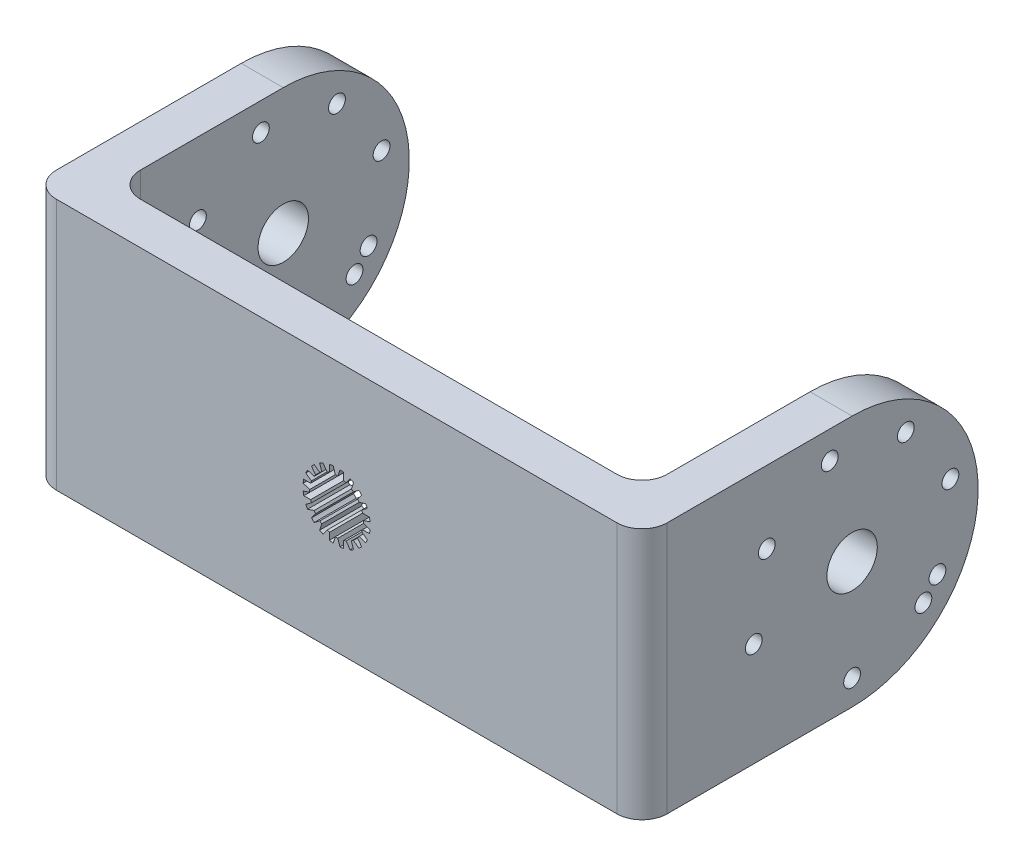
SolidWorks part; units mm, degrees
ref_plane "Front Plane" through (0, 0, 0) normal (0, 0, 1) x (1, 0, 0)
ref_plane "Top Plane" through (0, 0, 0) normal (0, 1, 0) x (1, 0, 0)
ref_plane "Right Plane" through (0, 0, 0) normal (1, 0, 0) x (0, 0, -1)
sketch "Sketch1" plane through (0, 0, 0) normal (0, 0, 1) x (1, 0, 0)
  line L0 (36.35, -15) -> (36.35, 15)
  line L1 (-36.35, -15) -> (-36.35, 15)
  line L2 (0, 0) -> (-36.35, 0)
  line L3 (0, 0) -> (36.35, 0)
  line L4 (-36.35, 15) -> (36.35, 15)
  line L5 (-36.35, -15) -> (36.35, -15)
  circle A0 centre (0, 0) radius 5
  point P10 (-36.35, 0)
  point P11 (36.35, 0)
  dimension "D1" = 10
  dimension "D2" = 30
  dimension "D4" = 36.35
  dimension "D5" = 36.35
extrude "Boss-Extrude1" add sketch "Sketch1" along normal blind 5 contours A0 L3 L0 L4 L1 L2 | L3 A0 L2 | L2 A0 L3 | A0 L2 L1 L5 L0 L3
sketch "Sketch4" plane through (0, 0, 0) normal (0, 0, -1) x (-1, 0, 0)
  line L0 (36.35, 15) -> (-36.35, 15) construction
  line L1 (-36.35, -15) -> (-31.35, -15)
  line L2 (-36.35, -15) -> (-36.35, 15)
  line L3 (-36.35, 15) -> (-31.35, 15)
  line L4 (-31.35, -15) -> (-31.35, 15)
  dimension "D1" = 5
extrude "Boss-Extrude4" add sketch "Sketch4" along normal blind 35
sketch "Sketch5" plane through (36.35, 0, 0) normal (1, 0, 0) x (0, 0, -1)
  line L0 (35, 0) -> (20, 0)
  line L1 (35, 15) -> (35, -15) construction
  circle A0 centre (20, 0) radius 15
  circle A1 centre (20, 0) radius 3
  dimension "D2" = 6
  dimension "D1" = 15
extrude "Cut-Extrude2" cut sketch "Sketch5" against normal blind 40
sketch "Sketch6" plane through (31.35, 0, 0) normal (-1, 0, 0) x (0, 0, 1)
  line L0 (-35, 15) -> (0, 15) construction
  line L1 (-35, -15) -> (0, -15) construction
  line L2 (-20, 15) -> (-35, 15)
  line L3 (-35, 15) -> (-35, -15)
  line L4 (-35, -15) -> (-20, -15)
  arc A0 (-20, 15) -> (-20, -15) centre (-20, 0) ccw
  circle A1 centre (-20, 0) radius 15 construction
  line M7 (0, 15) -> (-35, 15)
  line M8 (-35, 15) -> (-35, -15)
  line M9 (-35, -15) -> (0, -15)
extrude "Cut-Extrude3" cut sketch "Sketch6" against normal blind 10 contours A0 M7 M8 | A0 L3 M9
sketch "Sketch7" plane through (31.35, 0, 0) normal (-1, 0, 0) x (0, 0, 1)
  circle A0 centre (-31.7015, 2.6598) radius 1
  circle A1 centre (-17.3402, 11.7015) radius 1
  circle A2 centre (-9.845, 6.3935) radius 1
  circle A3 centre (-30.155, -6.3935) radius 1
  circle A4 centre (-8.2985, -2.6598) radius 1
  circle A6 centre (-26.3935, 10.155) radius 1
  circle A7 centre (-28.4853, -8.4853) radius 1
  circle A8 centre (-20, -12) radius 1
extrude "Cut-Extrude4" cut sketch "Sketch7" against normal blind 10
fillet "Fillet2" radius 3 1 edges at (36.35, 0, 5)
fillet "Fillet3" radius 3 1 edges at (31.35, 0, 0)
mirror "Mirror2" about plane through (0, 0, 0) normal (1, 0, 0) of "Cut-Extrude3", "Cut-Extrude2", "Boss-Extrude4", "Cut-Extrude4"
fillet "Fillet5" radius 3 1 edges at (-36.35, 0, 5)
fillet "Fillet6" radius 3 1 edges at (-31.35, 0, 0)
sketch "Sketch9" plane through (0, 0, 5) normal (0, 0, 1) x (1, 0, 0)
  line L0 (3.9776, 0.4069) -> (3.1976, 0.1569)
  line L1 (3.1976, 0.1569) -> (3.1976, -0.1431)
  line L2 (3.1976, -0.1431) -> (3.9776, -0.3931)
  line L3 (3.1976, 0.0069) -> (-0.0024, 0.0069) construction
  line L4 (3.9064, -0.8426) -> (3.0874, -0.8393)
  line L5 (3.0874, -0.8393) -> (2.9947, -1.1246)
  line L6 (2.9947, -1.1246) -> (3.6592, -1.6034)
  line L7 (3.4526, -2.0089) -> (2.6747, -1.7527)
  line L8 (2.6747, -1.7527) -> (2.4983, -1.9954)
  line L9 (2.4983, -1.9954) -> (2.9824, -2.6561)
  line L10 (2.6606, -2.9778) -> (1.9999, -2.4938)
  line L11 (1.9999, -2.4938) -> (1.7572, -2.6701)
  line L12 (1.7572, -2.6701) -> (2.0134, -3.4481)
  line L13 (1.6079, -3.6547) -> (1.1292, -2.9901)
  line L14 (1.1292, -2.9901) -> (0.8438, -3.0828)
  line L15 (0.8438, -3.0828) -> (0.8471, -3.9019)
  line L16 (0.3976, -3.9731) -> (0.1476, -3.1931)
  line L17 (0.1476, -3.1931) -> (-0.1524, -3.1931)
  line L18 (-0.1524, -3.1931) -> (-0.4024, -3.9731)
  line L19 (-0.8518, -3.9019) -> (-0.8485, -3.0828)
  line L20 (-0.8485, -3.0828) -> (-1.1339, -2.9901)
  line L21 (-1.1339, -2.9901) -> (-1.6126, -3.6547)
  line L22 (-2.0181, -3.4481) -> (-1.7619, -2.6701)
  line L23 (-1.7619, -2.6701) -> (-2.0046, -2.4938)
  line L24 (-2.0046, -2.4938) -> (-2.6653, -2.9778)
  line L25 (-2.9871, -2.6561) -> (-2.503, -1.9954)
  line L26 (-2.503, -1.9954) -> (-2.6794, -1.7527)
  line L27 (-2.6794, -1.7527) -> (-3.4573, -2.0089)
  line L28 (-3.6639, -1.6034) -> (-2.9994, -1.1246)
  line L29 (-2.9994, -1.1246) -> (-3.0921, -0.8393)
  line L30 (-3.0921, -0.8393) -> (-3.9111, -0.8426)
  line L31 (-3.9823, -0.3931) -> (-3.2024, -0.1431)
  line L32 (-3.2024, -0.1431) -> (-3.2024, 0.1569)
  line L33 (-3.2024, 0.1569) -> (-3.9823, 0.4069)
  line L34 (-3.9111, 0.8563) -> (-3.0921, 0.8531)
  line L35 (-3.0921, 0.8531) -> (-2.9994, 1.1384)
  line L36 (-2.9994, 1.1384) -> (-3.6639, 1.6172)
  line L37 (-3.4573, 2.0226) -> (-2.6794, 1.7664)
  line L38 (-2.6794, 1.7664) -> (-2.503, 2.0092)
  line L39 (-2.503, 2.0092) -> (-2.9871, 2.6699)
  line L40 (-2.6653, 2.9916) -> (-2.0046, 2.5076)
  line L41 (-2.0046, 2.5076) -> (-1.7619, 2.6839)
  line L42 (-1.7619, 2.6839) -> (-2.0181, 3.4619)
  line L43 (-1.6126, 3.6684) -> (-1.1339, 3.0039)
  line L44 (-1.1339, 3.0039) -> (-0.8485, 3.0966)
  line L45 (-0.8485, 3.0966) -> (-0.8518, 3.9157)
  line L46 (-0.4024, 3.9868) -> (-0.1524, 3.2069)
  line L47 (-0.1524, 3.2069) -> (0.1476, 3.2069)
  line L48 (0.1476, 3.2069) -> (0.3976, 3.9868)
  line L49 (0.8471, 3.9157) -> (0.8438, 3.0966)
  line L50 (0.8438, 3.0966) -> (1.1292, 3.0039)
  line L51 (1.1292, 3.0039) -> (1.6079, 3.6684)
  line L52 (2.0134, 3.4619) -> (1.7572, 2.6839)
  line L53 (1.7572, 2.6839) -> (1.9999, 2.5076)
  line L54 (1.9999, 2.5076) -> (2.6606, 2.9916)
  line L55 (2.9824, 2.6699) -> (2.4983, 2.0092)
  line L56 (2.4983, 2.0092) -> (2.6747, 1.7664)
  line L57 (2.6747, 1.7664) -> (3.4526, 2.0226)
  line L58 (3.6592, 1.6172) -> (2.9947, 1.1384)
  line L59 (2.9947, 1.1384) -> (3.0874, 0.8531)
  line L60 (3.0874, 0.8531) -> (3.9064, 0.8563)
  arc A0 (-2.6653, 2.9916) -> (-2.9871, 2.6699) centre (-0.0024, 0.0069) ccw
  arc A1 (-3.4573, 2.0226) -> (-3.6639, 1.6172) centre (-0.0024, 0.0069) ccw
  arc A2 (-3.9111, 0.8563) -> (-3.9823, 0.4069) centre (-0.0024, 0.0069) ccw
  arc A3 (-3.9823, -0.3931) -> (-3.9111, -0.8426) centre (-0.0024, 0.0069) ccw
  arc A4 (-3.6639, -1.6034) -> (-3.4573, -2.0089) centre (-0.0024, 0.0069) ccw
  arc A5 (-2.9871, -2.6561) -> (-2.6653, -2.9778) centre (-0.0024, 0.0069) ccw
  arc A6 (-2.0181, -3.4481) -> (-1.6126, -3.6547) centre (-0.0024, 0.0069) ccw
  arc A7 (-0.8518, -3.9019) -> (-0.4024, -3.9731) centre (-0.0024, 0.0069) ccw
  arc A8 (0.3976, -3.9731) -> (0.8471, -3.9019) centre (-0.0024, 0.0069) ccw
  arc A9 (1.6079, -3.6547) -> (2.0134, -3.4481) centre (-0.0024, 0.0069) ccw
  arc A10 (2.6606, -2.9778) -> (2.9824, -2.6561) centre (-0.0024, 0.0069) ccw
  arc A11 (3.4526, -2.0089) -> (3.6592, -1.6034) centre (-0.0024, 0.0069) ccw
  arc A12 (3.9064, -0.8426) -> (3.9776, -0.3931) centre (-0.0024, 0.0069) ccw
  arc A13 (3.9776, 0.4069) -> (3.9064, 0.8563) centre (-0.0024, 0.0069) ccw
  arc A14 (3.6592, 1.6172) -> (3.4526, 2.0226) centre (-0.0024, 0.0069) ccw
  arc A15 (2.9824, 2.6699) -> (2.6606, 2.9916) centre (-0.0024, 0.0069) ccw
  arc A16 (2.0134, 3.4619) -> (1.6079, 3.6684) centre (-0.0024, 0.0069) ccw
  arc A17 (0.8471, 3.9157) -> (0.3976, 3.9868) centre (-0.0024, 0.0069) ccw
  arc A18 (-0.4024, 3.9868) -> (-0.8518, 3.9157) centre (-0.0024, 0.0069) ccw
  arc A19 (-1.6126, 3.6684) -> (-2.0181, 3.4619) centre (-0.0024, 0.0069) ccw
  point P82 (-0.1581, 1.199)
  dimension "D1" = 0.3
  dimension "D2" = 0.8
  dimension "D3" = 3.2
extrude "Cut-Extrude5" cut sketch "Sketch9" against normal blind 5
equation "\"mm\"=35"
